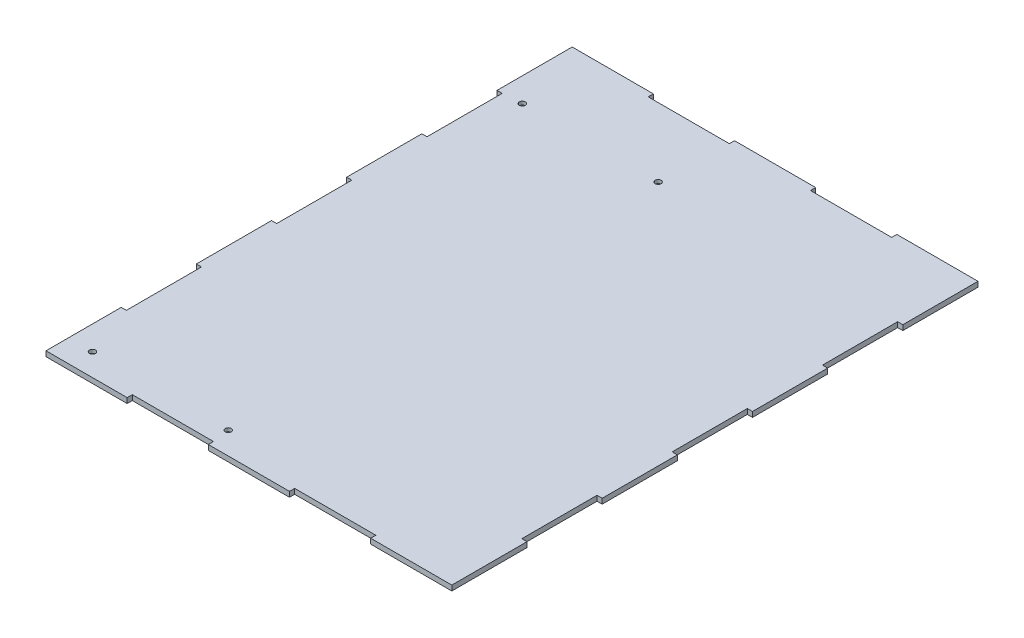
SolidWorks part; units mm, degrees
material "Pin"
ref_plane "Plan de face" through (0, 0, 0) normal (0, 0, 1) x (1, 0, 0)
ref_plane "Plan de dessus" through (0, 0, 0) normal (0, 1, 0) x (1, 0, 0)
ref_plane "Plan de droite" through (0, 0, 0) normal (1, 0, 0) x (0, 0, -1)
sketch "Esquisse1" plane through (0, 0, 0) normal (0, 1, 0) x (1, 0, 0)
  line L0 (-115, -150) -> (115, 150) construction
  line L1 (-70.8, 150) -> (-23.6, 150)
  line L2 (-115, 109.2857) -> (-115, 65.5714)
  line L3 (-70.8, -150) -> (-23.6, -150)
  line L4 (115, 109.2857) -> (115, 65.5714)
  line L5 (-118, 153) -> (-70.8, 153)
  line L6 (118, 153) -> (118, 109.2857)
  line L7 (-118, -153) -> (-70.8, -153)
  line L8 (-118, 153) -> (-118, 109.2857)
  line L9 (-70.8, 153) -> (-70.8, 150)
  line L10 (-23.6, 153) -> (-23.6, 150)
  line L11 (23.6, 153) -> (23.6, 150)
  line L12 (-70.8, -153) -> (-70.8, -150)
  line L13 (-23.6, 153) -> (23.6, 153)
  line L14 (70.8, 153) -> (70.8, 150)
  line L15 (-118, 153) -> (118, 153) construction
  line L16 (70.8, 153) -> (118, 153)
  line L17 (23.6, 150) -> (70.8, 150)
  line L18 (-23.6, -150) -> (-23.6, -153)
  line L19 (-115, 150) -> (115, 150) construction
  line L20 (23.6, -150) -> (23.6, -153)
  line L21 (70.8, -150) -> (70.8, -153)
  line L22 (23.6, -150) -> (70.8, -150)
  line L23 (-115, -150) -> (115, -150) construction
  line L24 (70.8, -153) -> (118, -153)
  line L25 (-23.6, -153) -> (23.6, -153)
  line L26 (-118, -153) -> (118, -153) construction
  line L27 (118, 109.2857) -> (115, 109.2857)
  line L28 (-118, 21.8571) -> (-115, 21.8571)
  line L29 (118, -21.8571) -> (115, -21.8571)
  line L30 (-118, -65.5714) -> (-115, -65.5714)
  line L31 (118, -109.2857) -> (115, -109.2857)
  line L32 (-118, 65.5714) -> (-115, 65.5714)
  line L33 (115, 65.5714) -> (118, 65.5714)
  line L34 (115, 21.8571) -> (118, 21.8571)
  line L35 (-115, -21.8571) -> (-118, -21.8571)
  line L36 (115, -65.5714) -> (118, -65.5714)
  line L37 (-115, -109.2857) -> (-118, -109.2857)
  line L38 (-115, 109.2857) -> (-118, 109.2857)
  line L39 (-118, 65.5714) -> (-118, 21.8571)
  line L40 (-115, 150) -> (-115, -150) construction
  line L41 (-115, 21.8571) -> (-115, -21.8571)
  line L42 (-118, 153) -> (-118, -153) construction
  line L43 (-118, -21.8571) -> (-118, -65.5714)
  line L44 (-115, -65.5714) -> (-115, -109.2857)
  line L45 (-118, -109.2857) -> (-118, -153)
  line L46 (118, -109.2857) -> (118, -153)
  line L47 (115, 150) -> (115, -150) construction
  line L48 (115, -65.5714) -> (115, -109.2857)
  line L49 (118, 153) -> (118, -153) construction
  line L50 (118, -21.8571) -> (118, -65.5714)
  line L51 (115, 21.8571) -> (115, -21.8571)
  line L52 (118, 65.5714) -> (118, 21.8571)
  point P38 (-115, -87.4286)
  dimension "D1" = 300
  dimension "D2" = 230
  dimension "D3" = 3
extrude "Boss.-Extru.1" add sketch "Esquisse1" along normal blind 3
hole_wizard "Diamètre du perçage Ø3.5 (3.5)1" positions "Esquisse2" profile "Esquisse3" hole size "Ø3.5" standard "Ansi Metric"
sketch "Esquisse2" plane through (0, 3, 0) normal (0, 1, 0) x (1, 0, 0)
  line L88 (-118, 153) -> (-118, 109.2857)
  line L89 (-118, 109.2857) -> (-115, 109.2857)
  line L90 (-115, 109.2857) -> (-115, 65.5714)
  line L91 (-115, 65.5714) -> (-118, 65.5714)
  line L92 (-118, 65.5714) -> (-118, 21.8571)
  line L93 (-118, 21.8571) -> (-115, 21.8571)
  line L94 (-115, 21.8571) -> (-115, -21.8571)
  line L95 (-115, -21.8571) -> (-118, -21.8571)
  line L96 (-118, -21.8571) -> (-118, -65.5714)
  line L97 (-118, -65.5714) -> (-115, -65.5714)
  line L98 (-115, -65.5714) -> (-115, -109.2857)
  line L99 (-115, -109.2857) -> (-118, -109.2857)
  line L100 (-118, -109.2857) -> (-118, -153)
  line L101 (-118, -153) -> (-70.8, -153)
  line L102 (-70.8, -153) -> (-70.8, -150)
  line L103 (-70.8, -150) -> (-23.6, -150)
  line L104 (-23.6, -150) -> (-23.6, -153)
  line L105 (-23.6, -153) -> (23.6, -153)
  line L106 (23.6, -153) -> (23.6, -150)
  line L107 (23.6, -150) -> (70.8, -150)
  line L108 (70.8, -150) -> (70.8, -153)
  line L109 (70.8, -153) -> (118, -153)
  line L110 (118, -153) -> (118, -109.2857)
  line L111 (118, -109.2857) -> (115, -109.2857)
  line L112 (115, -109.2857) -> (115, -65.5714)
  line L113 (115, -65.5714) -> (118, -65.5714)
  line L114 (118, -65.5714) -> (118, -21.8571)
  line L115 (118, -21.8571) -> (115, -21.8571)
  line L116 (115, -21.8571) -> (115, 21.8571)
  line L117 (115, 21.8571) -> (118, 21.8571)
  line L118 (118, 21.8571) -> (118, 65.5714)
  line L119 (118, 65.5714) -> (115, 65.5714)
  line L120 (115, 65.5714) -> (115, 109.2857)
  line L121 (115, 109.2857) -> (118, 109.2857)
  line L122 (118, 109.2857) -> (118, 153)
  line L123 (118, 153) -> (70.8, 153)
  line L124 (70.8, 153) -> (70.8, 150)
  line L125 (70.8, 150) -> (23.6, 150)
  line L126 (23.6, 150) -> (23.6, 153)
  line L127 (23.6, 153) -> (-23.6, 153)
  line L128 (-23.6, 153) -> (-23.6, 150)
  line L129 (-23.6, 150) -> (-70.8, 150)
  line L130 (-70.8, 150) -> (-70.8, 153)
  line L131 (-70.8, 153) -> (-118, 153)
  line L132 (-118, 153) -> (-118, 109.2857)
  line L133 (-118, 109.2857) -> (-115, 109.2857)
  line L134 (-115, 109.2857) -> (-115, 65.5714)
  line L135 (-115, 65.5714) -> (-118, 65.5714)
  line L136 (-118, 65.5714) -> (-118, 21.8571)
  line L137 (-118, 21.8571) -> (-115, 21.8571)
  line L138 (-115, 21.8571) -> (-115, -21.8571)
  line L139 (-115, -21.8571) -> (-118, -21.8571)
  line L140 (-118, -21.8571) -> (-118, -65.5714)
  line L141 (-118, -65.5714) -> (-115, -65.5714)
  line L142 (-115, -65.5714) -> (-115, -109.2857)
  line L143 (-115, -109.2857) -> (-118, -109.2857)
  line L144 (-118, -109.2857) -> (-118, -153)
  line L145 (-118, -153) -> (-70.8, -153)
  line L146 (-70.8, -153) -> (-70.8, -150)
  line L147 (-70.8, -150) -> (-23.6, -150)
  line L148 (-23.6, -150) -> (-23.6, -153)
  line L149 (-23.6, -153) -> (23.6, -153)
  line L150 (23.6, -153) -> (23.6, -150)
  line L151 (23.6, -150) -> (70.8, -150)
  line L152 (70.8, -150) -> (70.8, -153)
  line L153 (70.8, -153) -> (118, -153)
  line L154 (118, -153) -> (118, -109.2857)
  line L155 (118, -109.2857) -> (115, -109.2857)
  line L156 (115, -109.2857) -> (115, -65.5714)
  line L157 (115, -65.5714) -> (118, -65.5714)
  line L158 (118, -65.5714) -> (118, -21.8571)
  line L159 (118, -21.8571) -> (115, -21.8571)
  line L160 (115, -21.8571) -> (115, 21.8571)
  line L161 (115, 21.8571) -> (118, 21.8571)
  line L162 (118, 21.8571) -> (118, 65.5714)
  line L163 (118, 65.5714) -> (115, 65.5714)
  line L164 (115, 65.5714) -> (115, 109.2857)
  line L165 (115, 109.2857) -> (118, 109.2857)
  line L166 (118, 109.2857) -> (118, 153)
  line L167 (118, 153) -> (70.8, 153)
  line L168 (70.8, 153) -> (70.8, 150)
  line L169 (70.8, 150) -> (23.6, 150)
  line L170 (23.6, 150) -> (23.6, 153)
  line L171 (23.6, 153) -> (-23.6, 153)
  line L172 (-23.6, 153) -> (-23.6, 150)
  line L173 (-23.6, 150) -> (-70.8, 150)
  line L174 (-70.8, 150) -> (-70.8, 153)
  line L175 (-70.8, 153) -> (-118, 153)
  point P0 (-104, -140)
  point P3 (-25, -140)
  point P5 (-104, 110)
  point P7 (-25, 110)
  dimension "D1" = 0
sketch "Esquisse3" plane through (-104, 3, 140) normal (1, 0, 0) x (0, 0, 1)
  line L0 (0, 0) -> (0, 3.0515)
  line L1 (0, 3.0515) -> (1.75, 2)
  line L2 (1.75, 2) -> (1.75, 0)
  line L5 (1.75, 0) -> (0, 0)
  line L10 (0, 3.0515) -> (-1.75, 2) construction
  line L11 (0, -6.35) -> (0, 107.95) construction
  dimension "Diamètre du perçage" = 3.5
  dimension "Profondeur du perçage" = 2
  dimension "Angle de pointe" = 118
